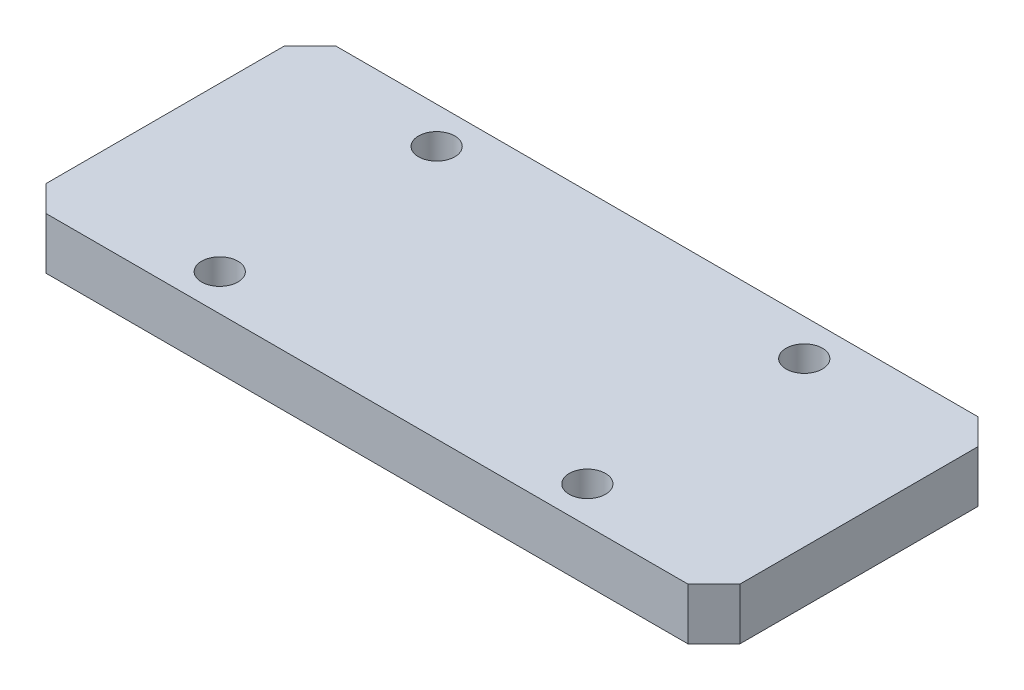
SolidWorks part; units mm, degrees
ref_plane "Front Plane" through (0, 0, 0) normal (0, 0, 1) x (1, 0, 0)
ref_plane "Top Plane" through (0, 0, 0) normal (0, 1, 0) x (1, 0, 0)
ref_plane "Right Plane" through (0, 0, 0) normal (1, 0, 0) x (0, 0, -1)
sketch "Sketch2" plane through (0, 0, 0) normal (0, 0, 1) x (1, 0, 0)
  line L0 (46, 10) -> (-46, 10)
  line L14 (-45, 0) -> (45, 0)
  line L20 (-46, 10) -> (-67, 10)
  line L21 (-67, 10) -> (-67, 0)
  line L22 (-67, 0) -> (-45, 0)
  line L23 (46, 10) -> (67, 10)
  line L24 (67, 10) -> (67, 0)
  line L25 (67, 0) -> (45, 0)
  point P3 (46.1795, 10)
  point P4 (0, 10)
  point P17 (50, 10)
  point P20 (47, 0)
  point P23 (-47, 0)
  point P26 (-50, 10)
  dimension "D9" = 10
  dimension "D1" = 100
  dimension "D2" = 10
extrude "Boss-Extrude1" add sketch "Sketch2" along normal blind 56
sketch "Sketch3" plane through (0, 10, 0) normal (0, 1, 0) x (1, 0, 0)
  line L1 (67, 0) -> (-67, 0) construction
  line L2 (-67, -56) -> (-67, 0) construction
  circle A0 centre (-35.5, -7.055) radius 3.5
  circle A1 centre (35.5, -7.055) radius 3.5
  circle A2 centre (-35.5, -48.945) radius 3.5
  circle A3 centre (35.5, -48.945) radius 3.5
  dimension "D1" = 7
  dimension "D2" = 7
  dimension "D4" = 31.5
  dimension "D5" = 7
  dimension "D6" = 7
  dimension "D3" = 71
  dimension "D7" = 41.89
  dimension "D8" = 7.055
extrude "Cut-Extrude1" cut sketch "Sketch3" against normal blind 10
chamfer "Chamfer1" distance 5 angle 45 4 edges at (-67, 5, 0) (-67, 5, 56) (67, 5, 0) (67, 5, 56)
